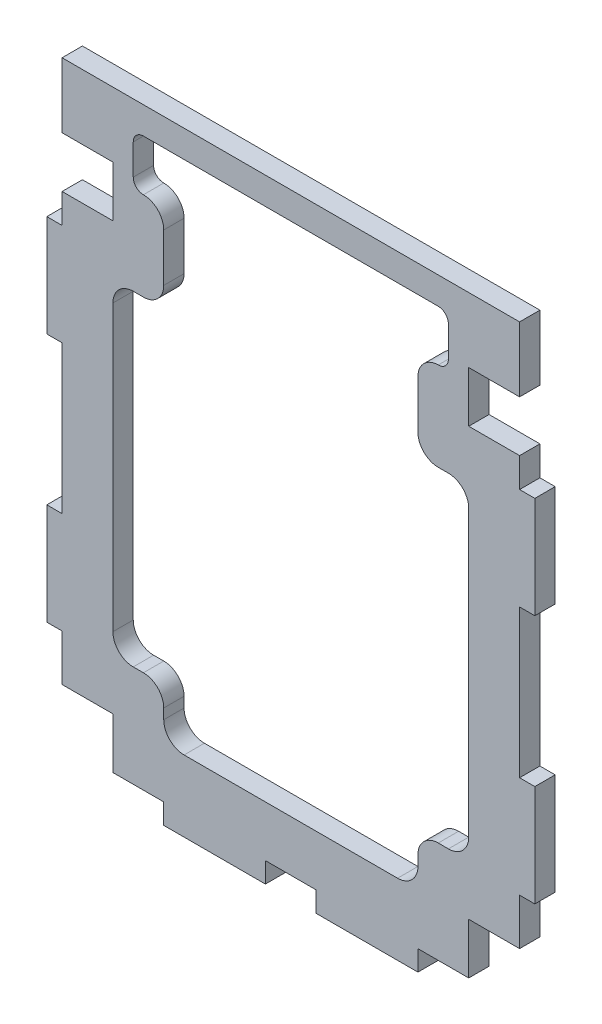
SolidWorks part; units mm, degrees
ref_plane "前视基准面" through (0, 0, 0) normal (0, 0, 1) x (1, 0, 0)
ref_plane "上视基准面" through (0, 0, 0) normal (0, 1, 0) x (1, 0, 0)
ref_plane "右视基准面" through (0, 0, 0) normal (1, 0, 0) x (0, 0, -1)
sketch "Model" plane through (0, 0, 0) normal (0, 0, 1) x (1, 0, 0)
  line L0 (973.665, 622.0235) -> (973.665, 615.6331)
  line L1 (973.665, 610.6331) -> (973.665, 607.7409)
  line L2 (973.665, 597.7409) -> (973.665, 583.1907)
  line L3 (973.665, 573.1907) -> (973.665, 568.6331)
  line L4 (973.665, 583.1907) -> (972.165, 583.1907)
  line L5 (973.665, 573.1907) -> (972.165, 573.1907)
  line L6 (973.665, 607.7409) -> (972.165, 607.7409)
  line L7 (973.665, 597.7409) -> (972.165, 597.7409)
  line L8 (973.665, 615.6331) -> (978.665, 615.6331)
  line L9 (978.665, 615.6331) -> (978.665, 610.6331)
  line L10 (978.665, 610.6331) -> (973.665, 610.6331)
  line L11 (973.665, 568.6331) -> (978.665, 568.6331)
  line L12 (978.665, 568.6331) -> (978.665, 563.6331)
  line L13 (972.165, 607.7409) -> (972.165, 597.7409)
  line L14 (972.165, 583.1907) -> (972.165, 573.1907)
  line L15 (1018.665, 622.0235) -> (973.665, 622.0235)
  line L16 (998.665, 563.6331) -> (993.665, 563.6331)
  line L17 (983.665, 563.6331) -> (978.665, 563.6331)
  line L18 (993.665, 561.6331) -> (983.665, 561.6331)
  line L19 (983.665, 563.6331) -> (983.665, 561.6331)
  line L20 (993.665, 561.6331) -> (993.665, 563.6331)
  line L21 (980.665, 605.6331) -> (981.665, 605.6331)
  line L22 (983.665, 607.6331) -> (983.665, 612.3531)
  line L23 (980.665, 573.6331) -> (981.665, 573.6331)
  line L24 (983.665, 571.6331) -> (983.665, 570.6331)
  line L25 (985.665, 568.6331) -> (1006.665, 568.6331)
  line L26 (981.665, 619.3531) -> (1010.665, 619.3531)
  line L27 (1018.665, 622.0235) -> (1018.665, 615.6331)
  line L28 (1018.665, 610.6331) -> (1018.665, 607.7409)
  line L29 (1018.665, 597.7409) -> (1018.665, 583.1907)
  line L30 (1018.665, 573.1907) -> (1018.665, 568.6331)
  line L31 (1018.665, 583.1907) -> (1020.165, 583.1907)
  line L32 (1018.665, 573.1907) -> (1020.165, 573.1907)
  line L33 (1018.665, 607.7409) -> (1020.1659, 607.7409)
  line L34 (1018.665, 597.7409) -> (1020.1659, 597.7409)
  line L35 (1018.665, 615.6331) -> (1013.665, 615.6331)
  line L36 (1013.665, 615.6331) -> (1013.665, 610.6331)
  line L37 (1013.665, 610.6331) -> (1018.665, 610.6331)
  line L38 (1018.665, 568.6331) -> (1013.665, 568.6331)
  line L39 (1013.665, 568.6331) -> (1013.665, 563.6331)
  line L40 (1020.1659, 607.7409) -> (1020.1659, 597.7409)
  line L41 (1020.165, 583.1907) -> (1020.165, 573.1907)
  line L42 (1008.665, 563.6331) -> (1013.665, 563.6331)
  line L43 (998.665, 561.6331) -> (1008.665, 561.6331)
  line L44 (1008.665, 563.6331) -> (1008.665, 561.6331)
  line L45 (998.665, 561.6331) -> (998.665, 563.6331)
  line L46 (1011.665, 605.6331) -> (1010.665, 605.6331)
  line L47 (1008.665, 607.6331) -> (1008.665, 612.3531)
  line L48 (1011.665, 573.6331) -> (1010.665, 573.6331)
  line L49 (1008.665, 571.6331) -> (1008.665, 570.6331)
  line L50 (1013.665, 603.6331) -> (1013.665, 575.6331)
  line L51 (978.665, 603.6331) -> (978.665, 575.6331)
  line L52 (980.665, 615.3531) -> (980.665, 618.3531)
  line L53 (1011.665, 615.3531) -> (1011.665, 618.3531)
  arc A0 (980.665, 605.6331) -> (978.665, 603.6331) centre (980.665, 603.6331) ccw
  arc A1 (978.665, 575.6331) -> (980.665, 573.6331) centre (980.665, 575.6331) ccw
  arc A2 (983.665, 612.3531) -> (981.665, 614.3531) centre (981.665, 612.3531) ccw
  arc A3 (981.665, 605.6331) -> (983.665, 607.6331) centre (981.665, 607.6331) ccw
  arc A4 (983.665, 571.6331) -> (981.665, 573.6331) centre (981.665, 571.6331) ccw
  arc A5 (983.665, 570.6331) -> (985.665, 568.6331) centre (985.665, 570.6331) ccw
  arc A6 (981.665, 619.3531) -> (980.665, 618.3531) centre (981.665, 618.3531) ccw
  arc A7 (1013.665, 603.6331) -> (1011.665, 605.6331) centre (1011.665, 603.6331) ccw
  arc A8 (1011.665, 573.6331) -> (1013.665, 575.6331) centre (1011.665, 575.6331) ccw
  arc A9 (1010.665, 614.3531) -> (1008.665, 612.3531) centre (1010.665, 612.3531) ccw
  arc A10 (1008.665, 607.6331) -> (1010.665, 605.6331) centre (1010.665, 607.6331) ccw
  arc A11 (1010.665, 573.6331) -> (1008.665, 571.6331) centre (1010.665, 571.6331) ccw
  arc A12 (1006.665, 568.6331) -> (1008.665, 570.6331) centre (1006.665, 570.6331) ccw
  arc A13 (1011.665, 618.3531) -> (1010.665, 619.3531) centre (1010.665, 618.3531) ccw
  arc A14 (980.665, 615.3531) -> (981.665, 614.3531) centre (981.665, 615.3531) ccw
  arc A15 (1010.665, 614.3531) -> (1011.665, 615.3531) centre (1010.665, 615.3531) ccw
extrude "凸台-拉伸1" add sketch "Model" along normal blind 2
